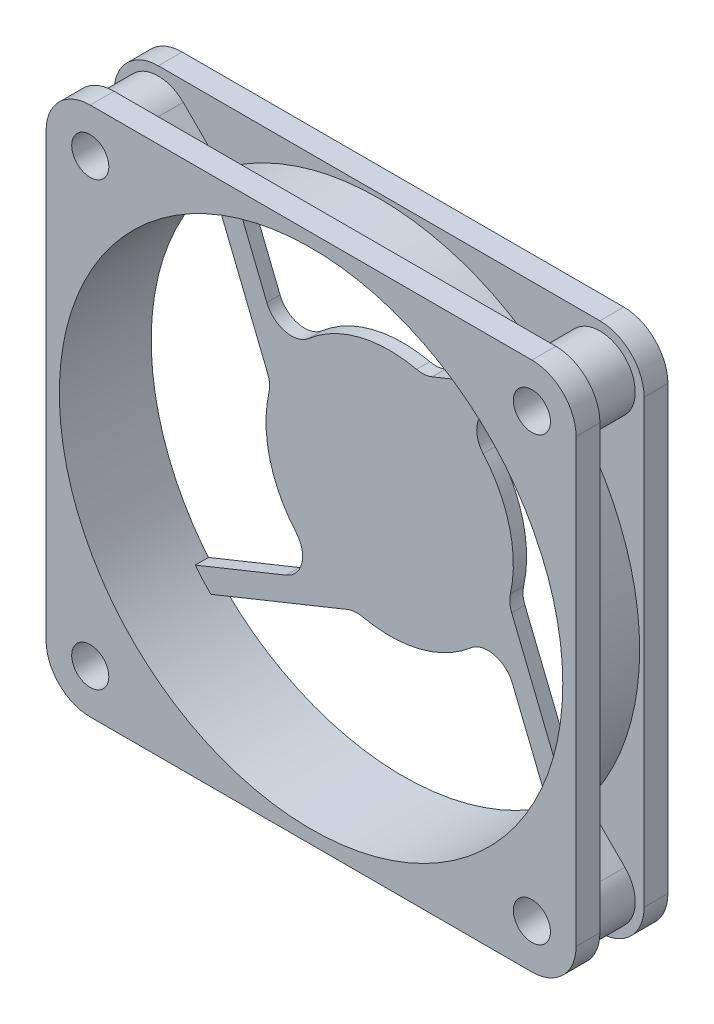
SolidWorks part; units mm, degrees
ref_plane "Plan de face" through (0, 0, 0) normal (0, 0, 1) x (1, 0, 0)
ref_plane "Plan de dessus" through (0, 0, 0) normal (0, 1, 0) x (1, 0, 0)
ref_plane "Plan de droite" through (0, 0, 0) normal (1, 0, 0) x (0, 0, -1)
sketch "Esquisse1" plane through (0, 0, 0) normal (0, 0, 1) x (1, 0, 0)
  line L0 (-7.4442, 0) -> (91.4349, 0) construction
  line L1 (0, -8.2025) -> (0, 89.633) construction
  line L2 (-7.4442, 60) -> (91.4349, 60) construction
  line L3 (60, -8.2025) -> (60, 89.633) construction
  line L4 (30, 83.276) -> (30, 25.3092) construction
  line L5 (86.1442, 30) -> (25.1605, 30) construction
  line L6 (79.7873, 55) -> (52.2045, 55) construction
  line L7 (55, 75.1951) -> (55, 52.03) construction
  line L9 (5, 60) -> (55, 60)
  line L10 (0, 55) -> (0, 5)
  line L11 (5, 0) -> (55, 0)
  line L12 (60, 55) -> (60, 5)
  circle A0 centre (30, 30) radius 28.5
  circle A1 centre (55, 55) radius 2.1
  circle A2 centre (5, 55) radius 2.1
  circle A3 centre (55, 5) radius 2.1
  circle A4 centre (5, 5) radius 2.1
  arc A5 (55, 60) -> (60, 55) centre (55, 55) cw
  arc A6 (55, 0) -> (60, 5) centre (55, 5) ccw
  arc A7 (0, 5) -> (5, 0) centre (5, 5) ccw
  arc A8 (5, 60) -> (0, 55) centre (5, 55) ccw
  point P35 (60, 0)
  point P40 (0, 60)
  dimension "D7" = 5
  dimension "D1" = 60
  dimension "D2" = 60
  dimension "D3" = 30
  dimension "D4" = 30
  dimension "D5" = 5
  dimension "D6" = 5
extrude "Boss.-Extru.1" add sketch "Esquisse1" along normal blind 10.4
ref_plane "Plan1" through (0, 0, 5.2) normal (0, 0, 1) x (1, 0, 0)
sketch "Esquisse2" plane through (0, 0, 5.2) normal (0, 0, 1) x (1, 0, 0)
  line L0 (30, 26.4746) -> (30, 77.2899) construction
  line L1 (41.3304, 30) -> (-17.4551, 30) construction
  line L2 (30, 30) -> (-4.049, 64.049) construction
  line L3 (-7.1656, 61.5087) -> (11.4372, 42.906) construction
  line L4 (2.1716, 52.1716) -> (6.5046, 47.8386)
  line L5 (7.8284, 57.8284) -> (12.1614, 53.4954)
  line L6 (52.1716, 57.8284) -> (47.8386, 53.4954)
  line L7 (57.8284, 52.1716) -> (53.4954, 47.8386)
  line L8 (57.8284, 7.8284) -> (53.4954, 12.1614)
  line L9 (52.1716, 2.1716) -> (47.8386, 6.5046)
  line L10 (7.8284, 2.1716) -> (12.1614, 6.5046)
  line L11 (2.1716, 7.8284) -> (6.5046, 12.1614)
  line L13 (5, 0) -> (55, 0)
  line L14 (0, 5) -> (0, 55)
  line L15 (5, 60) -> (55, 60)
  line L16 (60, 5) -> (60, 55)
  line L17 (0, 0) -> (60, 60) construction
  line L18 (0, 60) -> (60, 0) construction
  arc A0 (7.8284, 57.8284) -> (2.1716, 52.1716) centre (5, 55) ccw
  arc A1 (6.5046, 47.8386) -> (6.5046, 12.1614) centre (30, 30) ccw
  arc A2 (57.8284, 52.1716) -> (52.1716, 57.8284) centre (55, 55) ccw
  arc A3 (52.1716, 2.1716) -> (57.8284, 7.8284) centre (55, 5) ccw
  arc A4 (2.1716, 7.8284) -> (7.8284, 2.1716) centre (5, 5) ccw
  arc A5 (12.1614, 6.5046) -> (47.8386, 6.5046) centre (30, 30) ccw
  arc A6 (53.4954, 12.1614) -> (53.4954, 47.8386) centre (30, 30) ccw
  arc A7 (47.8386, 53.4954) -> (12.1614, 53.4954) centre (30, 30) ccw
  arc A8 (55, 0) -> (60, 5) centre (55, 5) ccw
  arc A9 (5, 0) -> (0, 5) centre (5, 5) cw
  arc A10 (0, 55) -> (5, 60) centre (5, 55) cw
  arc A11 (55, 60) -> (60, 55) centre (55, 55) cw
  dimension "D1" = 45
  dimension "D2" = 4
  dimension "D4" = 5
  dimension "D3" = 4
extrude "Enlèv. mat.-Extru.1" cut sketch "Esquisse2" against normal mid plane 5
sketch "Esquisse3" plane through (0, 0, 0) normal (0, 0, -1) x (-1, 0, 0)
  line L0 (-28.11, 72.0505) -> (-61.9121, -11.6128) construction
  line L1 (10.9837, 0) -> (-84.9442, 0) construction
  line L2 (-25.4272, 70.6822) -> (-56.8555, -7.1055) construction
  line L3 (-22.7819, 70.5558) -> (-54.5283, -8.0193) construction
  line L4 (-43.9069, 18.2697) -> (-48.0715, 7.962)
  line L5 (-43.8116, 25.1792) -> (-50.048, 9.7435)
  line L6 (-41.7303, 43.9069) -> (-52.038, 48.0715)
  line L7 (-34.8208, 43.8116) -> (-50.2565, 50.048)
  line L8 (-16.0931, 41.7303) -> (-11.9285, 52.038)
  line L9 (-16.1884, 34.8208) -> (-9.952, 50.2565)
  line L10 (-18.2697, 16.0931) -> (-7.962, 11.9285)
  line L11 (-25.1792, 16.1884) -> (-9.7435, 9.952)
  arc A0 (-39.162, 19.4143) -> (-26.9555, 16.3351) centre (-30, 30) ccw
  arc A1 (-9.7435, 9.952) -> (-7.962, 11.9285) centre (-30, 30) ccw
  arc A2 (-9.952, 50.2565) -> (-11.9285, 52.038) centre (-30, 30) ccw
  arc A3 (-43.6649, 26.9555) -> (-43.8116, 25.1792) centre (-46.5931, 26.3031) cw
  arc A4 (-50.2565, 50.048) -> (-52.038, 48.0715) centre (-30, 30) ccw
  arc A5 (-50.048, 9.7435) -> (-48.0715, 7.962) centre (-30, 30) ccw
  arc A6 (-20.838, 40.5857) -> (-33.0445, 43.6649) centre (-30, 30) ccw
  arc A7 (-19.4143, 20.838) -> (-16.3351, 33.0445) centre (-30, 30) ccw
  arc A8 (-40.5857, 39.162) -> (-43.6649, 26.9555) centre (-30, 30) ccw
  arc A9 (-16.1884, 34.8208) -> (-16.3351, 33.0445) centre (-13.4069, 33.6969) ccw
  arc A10 (-25.1792, 16.1884) -> (-26.9555, 16.3351) centre (-26.3031, 13.4069) ccw
  arc A11 (-34.8208, 43.8116) -> (-33.0445, 43.6649) centre (-33.6969, 46.5931) ccw
  arc A12 (-16.0931, 41.7303) -> (-20.838, 40.5857) centre (-18.8747, 42.8541) cw
  arc A13 (-18.2697, 16.0931) -> (-19.4143, 20.838) centre (-17.1459, 18.8747) cw
  arc A14 (-43.9069, 18.2697) -> (-39.162, 19.4143) centre (-41.1253, 17.1459) cw
  arc A15 (-41.7303, 43.9069) -> (-40.5857, 39.162) centre (-42.8541, 41.1253) cw
  point P31 (-43.4432, 26.091)
  point P44 (-42.0483, 22.8699)
  dimension "D1" = 68
  dimension "D4" = 4
  dimension "D5" = 3
  dimension "D6" = 3
  dimension "D2" = 3
  dimension "D3" = 2.5
extrude "Boss.-Extru.2" add sketch "Esquisse3" against normal blind 1.5 separate body
